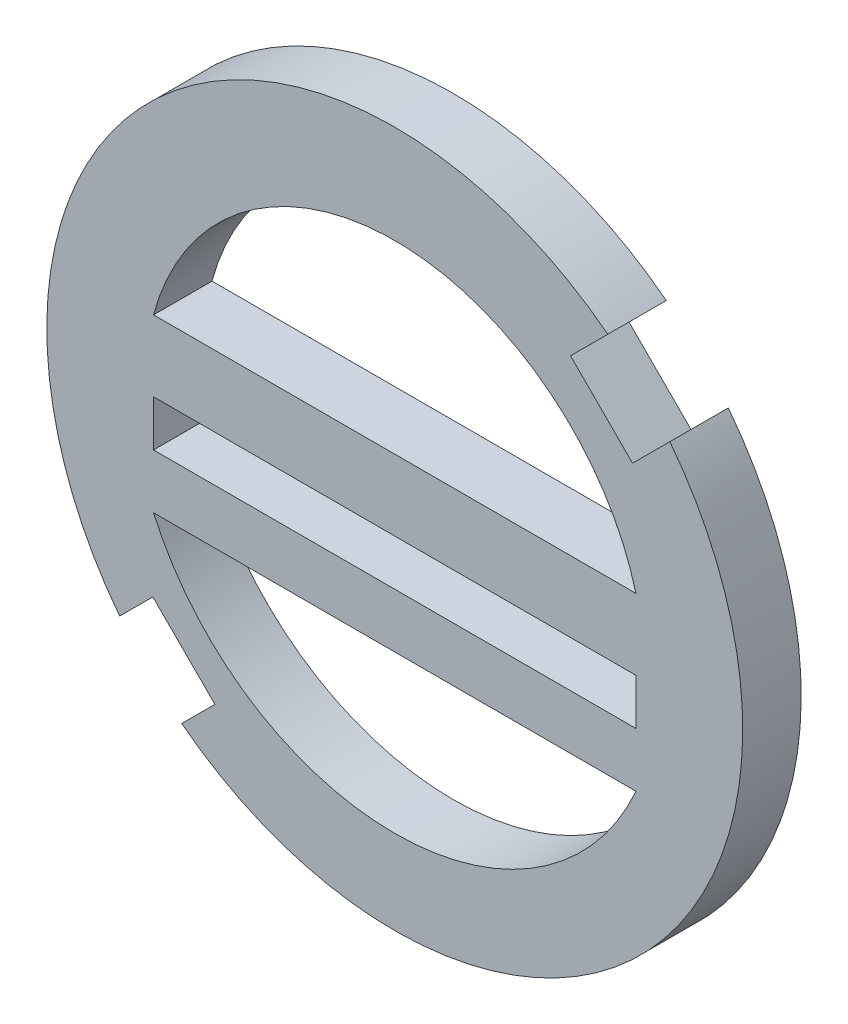
SolidWorks part; units mm, degrees
ref_plane "Front Plane" through (0, 0, 0) normal (0, 0, 1) x (1, 0, 0)
ref_plane "Top Plane" through (0, 0, 0) normal (0, 1, 0) x (1, 0, 0)
ref_plane "Right Plane" through (0, 0, 0) normal (1, 0, 0) x (0, 0, -1)
sketch "Sketch1" plane through (0, 0, 0) normal (0, 0, 1) x (1, 0, 0)
  line L0 (-52.3875, 14.0556) -> (52.3875, 14.0556)
  line L1 (-52.3875, -1.35) -> (52.3875, -1.35)
  line L2 (-52.3875, -1.35) -> (-52.3875, -11.35)
  line L3 (-52.3875, -11.35) -> (52.3875, -11.35)
  line L4 (52.3875, -1.35) -> (52.3875, -11.35)
  line L5 (-52.3875, -23.1545) -> (52.3875, -23.1545)
  circle A0 centre (0, 0) radius 75.565
  arc A1 (-52.3875, 14.0556) -> (52.3875, 14.0556) centre (0, 0) cw
  arc A2 (-52.3875, -23.1545) -> (52.3875, -23.1545) centre (0, 0) ccw
  point P7 (-52.3875, -6.35)
  point P10 (0, -1.35)
  point P12 (0, 0)
  point P13 (0, 0)
  point P14 (0, 0)
  dimension "D1" = 151.13
  dimension "D2" = 6.35
  dimension "D3" = 10
  dimension "D4" = 104.775
extrude "Boss-Extrude1" add sketch "Sketch1" along normal blind 12.7
sketch "Sketch2" [suppressed] plane through (0, 0, 12.7) normal (0, 0, 1) x (1, 0, 0)
  line L0 (48.6383, 57.8307) -> (57.8307, 48.6383)
  line L1 (57.8307, 48.6383) -> (-48.6383, -57.8307)
  line L2 (-48.6383, -57.8307) -> (-57.8307, -48.6383)
  line L3 (-57.8307, -48.6383) -> (48.6383, 57.8307)
  line L4 (0, 0) -> (125.4112, 0) construction
  line L5 (53.2345, 53.2345) -> (-53.2345, -53.2345) construction
  circle A2 centre (0, 0) radius 75.565 construction
  point P10 (54.4563, 45.2639)
  point P11 (0, 0)
  point P12 (0, 0)
  point P15 (0, 0)
  dimension "D1" = 6.5
  dimension "D3" = 6.5
  dimension "D4" = 45
sketch "Sketch3" plane through (0, 0, 12.7) normal (0, 0, 1) x (1, 0, 0)
  line L0 (47.1463, 60.6167) -> (60.6167, 47.1463)
  line L1 (60.6167, 47.1463) -> (51.6365, 38.1661)
  line L2 (51.6365, 38.1661) -> (38.1661, 51.6365)
  line L3 (38.1661, 51.6365) -> (47.1463, 60.6167)
  line L4 (-52.5345, -39.0641) -> (-39.0641, -52.5345)
  line L5 (-39.0641, -52.5345) -> (-48.0444, -61.5148)
  line L6 (-48.0444, -61.5148) -> (-61.5148, -48.0444)
  line L7 (-61.5148, -48.0444) -> (-52.5345, -39.0641)
  line L8 (0, 0) -> (123.8793, 0) construction
  line L9 (-59.7825, -59.7825) -> (59.093, 59.093) construction
  point P12 (53.8815, 53.8815)
  point P13 (-54.7796, -54.7796)
  point P14 (-35.3155, -47.4105)
  point P15 (-29.2646, -48.2907)
  point P18 (58.9692, 36.8626)
  point P19 (-19.033, -39.8193)
  point P20 (0, 0)
  dimension "D1" = 64.77
  dimension "D2" = 12.7
  dimension "D3" = 19.05
  dimension "D4" = 63.5
  dimension "D5" = 45
extrude "Cut-Extrude1" cut sketch "Sketch3" against normal blind 12.7
